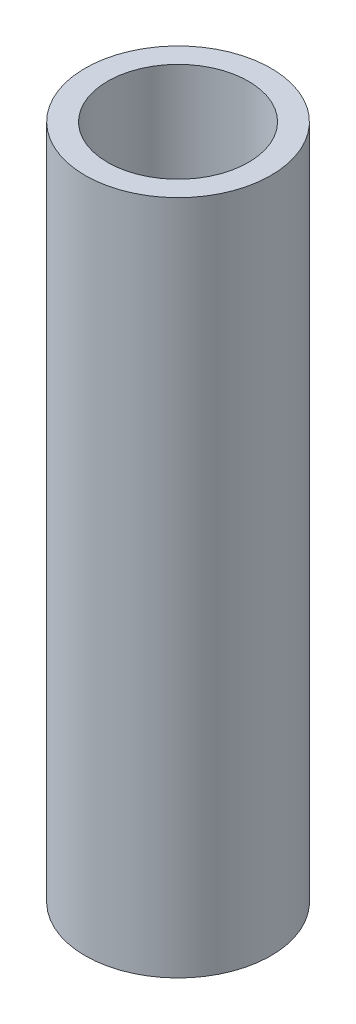
SolidWorks part; units mm, degrees
ref_plane "Front Plane" through (0, 0, 0) normal (0, 0, 1) x (1, 0, 0)
ref_plane "Top Plane" through (0, 0, 0) normal (0, 1, 0) x (1, 0, 0)
ref_plane "Right Plane" through (0, 0, 0) normal (1, 0, 0) x (0, 0, -1)
sketch "Sketch1" plane through (0, 0, 0) normal (0, 1, 0) x (1, 0, 0)
  circle A0 centre (0, 0) radius 0.825
  circle A1 centre (0, 0) radius 0.625
  dimension "D1" = 1.65
  dimension "D2" = 1.25
extrude "Boss-Extrude1" add sketch "Sketch1" along normal blind 6 contours A1 | A0
